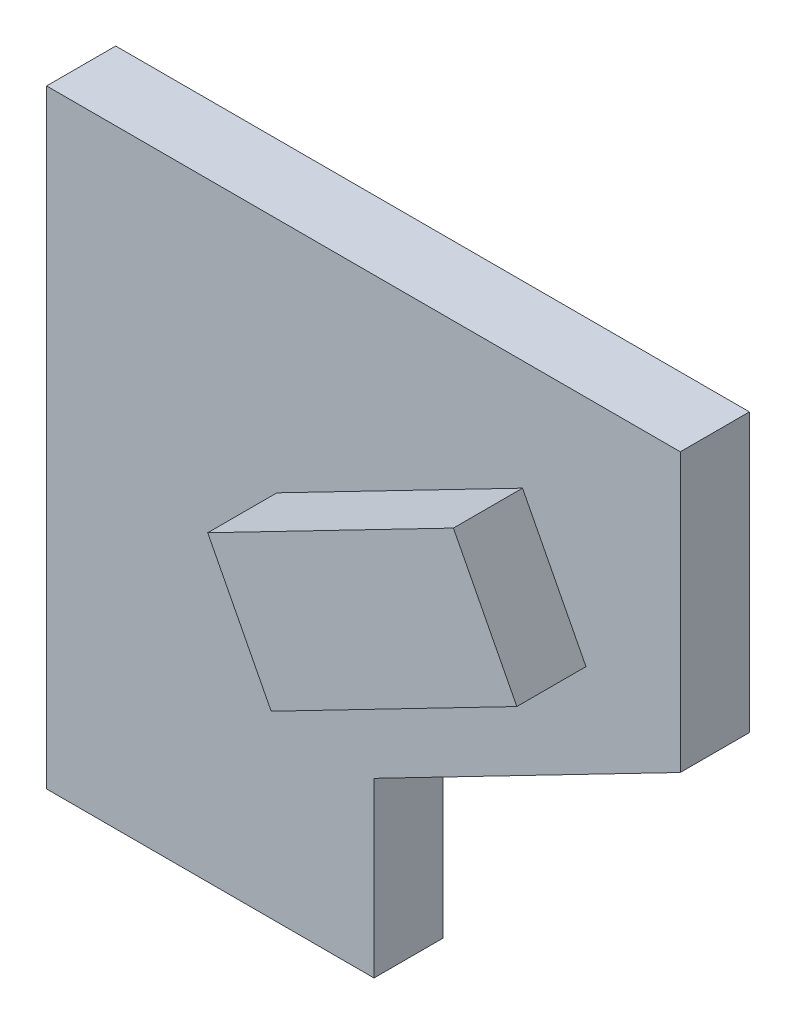
SolidWorks part; units mm, degrees
ref_plane "Front Plane" through (0, 0, 0) normal (0, 0, 1) x (1, 0, 0)
ref_plane "Top Plane" through (0, 0, 0) normal (0, 1, 0) x (1, 0, 0)
ref_plane "Right Plane" through (0, 0, 0) normal (1, 0, 0) x (0, 0, -1)
sketch "Sketch1" plane through (0, 0, 0) normal (0, 0, 1) x (1, 0, 0)
  line L0 (-21.9528, -30.0686) -> (25.412, -30.0686)
  line L1 (25.412, -30.0686) -> (25.412, -5.0558)
  line L2 (25.412, -5.0558) -> (69.7167, 17.8283)
  line L3 (69.7167, 17.8283) -> (69.7167, 58.0085)
  line L4 (69.7167, 58.0085) -> (-21.9528, 58.0085)
  line L5 (-21.9528, 58.0085) -> (-21.9528, -30.0686)
extrude "Boss-Extrude1" add sketch "Sketch1" along normal blind 10
sketch "Sketch4" plane through (25.412, -5.0558, 10) normal (0, 0, 1) x (0.8885, 0.4589, 0)
  line L1 (0.701, 31.9845) -> (40.701, 31.9845)
  line L2 (0.701, 31.9845) -> (0.701, 11.9845)
  line L3 (0.701, 11.9845) -> (40.701, 11.9845)
  line L4 (40.701, 31.9845) -> (40.701, 11.9845)
  line L5 (0.701, 31.9845) -> (40.701, 11.9845) construction
  line L6 (0.701, 11.9845) -> (40.701, 31.9845) construction
  point P0 (20.701, 21.9845)
  point P5 (0.701, 31.9845)
  dimension "D1" = 20
  dimension "D2" = 40
extrude "Boss-Extrude2" add sketch "Sketch4" along normal blind 10
